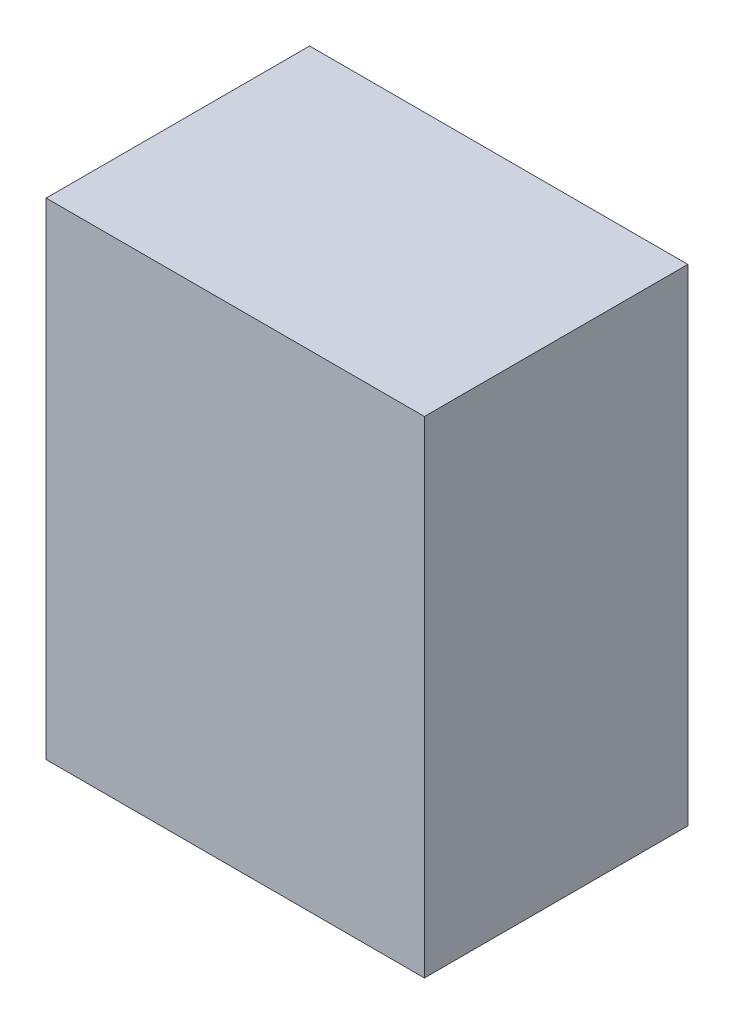
SolidWorks part; units mm, degrees
ref_plane "前视基准面" through (0, 0, 0) normal (0, 0, 1) x (1, 0, 0)
ref_plane "上视基准面" through (0, 0, 0) normal (0, 1, 0) x (1, 0, 0)
ref_plane "右视基准面" through (0, 0, 0) normal (1, 0, 0) x (0, 0, -1)
sketch "草图1" plane through (0, 0, 0) normal (0, 0, 1) x (1, 0, 0)
  line L1 (-28, 36) -> (28, 36)
  line L2 (-28, 36) -> (-28, -36)
  line L3 (-28, -36) -> (28, -36)
  line L4 (28, 36) -> (28, -36)
  line L5 (-28, 36) -> (28, -36) construction
  line L6 (-28, -36) -> (28, 36) construction
  point P0 (0, 0)
  dimension "D1" = 56
  dimension "D2" = 72
extrude "凸台-拉伸1" add sketch "草图1" along normal blind 39
